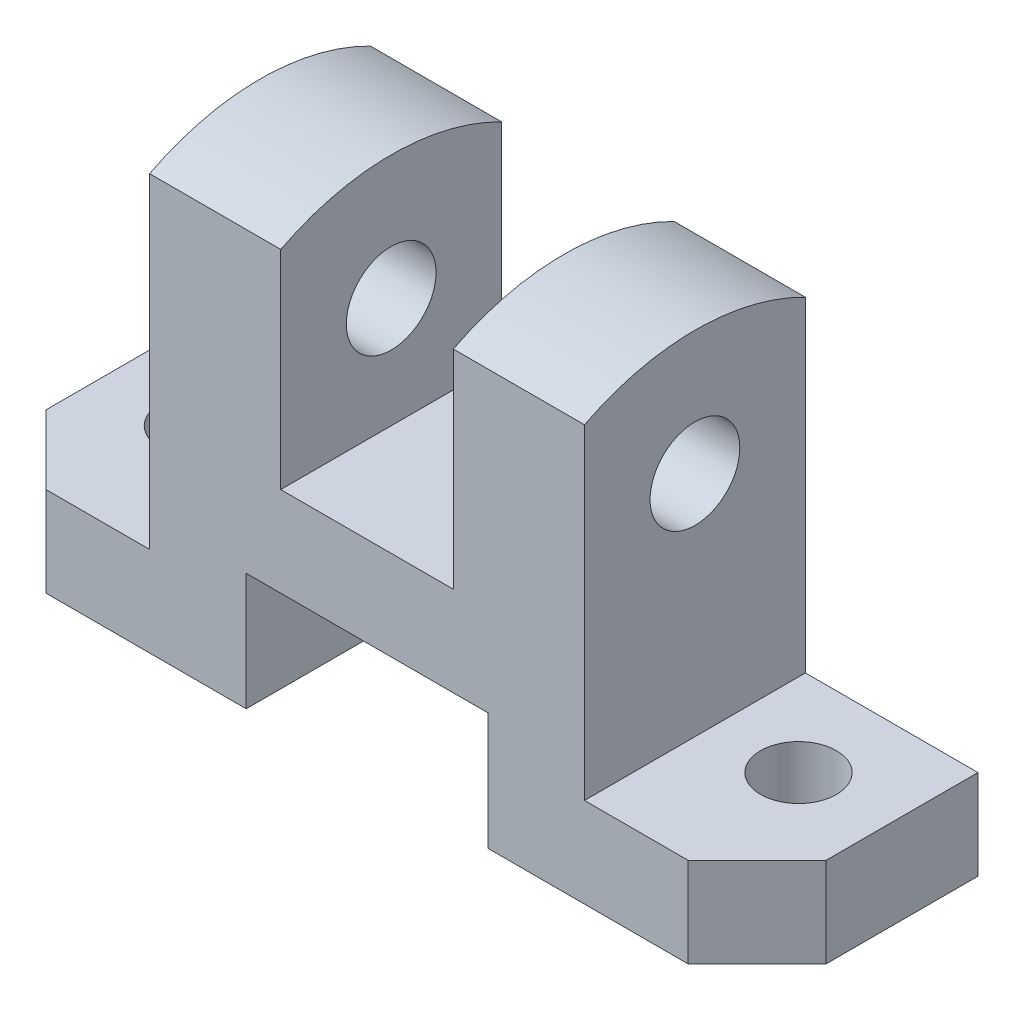
SolidWorks part; units mm, degrees
ref_plane "Front Plane" through (0, 0, 0) normal (0, 0, 1) x (1, 0, 0)
ref_plane "Top Plane" through (0, 0, 0) normal (0, 1, 0) x (1, 0, 0)
ref_plane "Right Plane" through (0, 0, 0) normal (1, 0, 0) x (0, 0, -1)
sketch "Sketch2" plane through (0, 0, 0) normal (0, 1, 0) x (1, 0, 0)
  line L0 (0, 31.6429) -> (0, -36.0714) construction
  line L1 (17.5, 0) -> (56.5, 0)
  line L2 (56.5, 0) -> (56.5, -22)
  line L3 (56.5, -22) -> (46.5, -32)
  line L4 (46.5, -32) -> (17.5, -32)
  line L5 (17.5, 0) -> (17.5, -32)
  line L6 (-17.5, 0) -> (-17.5, -32)
  line L7 (-46.5, -32) -> (-17.5, -32)
  line L8 (-56.5, -22) -> (-46.5, -32)
  line L9 (-56.5, 0) -> (-56.5, -22)
  line L10 (-17.5, 0) -> (-56.5, 0)
  circle A0 centre (43.5, -13) radius 5.5
  circle A1 centre (-43.5, -13) radius 5.5
  dimension "D7" = 11
  dimension "D1" = 10
  dimension "D2" = 39
  dimension "D3" = 32
  dimension "D4" = 45
  dimension "D5" = 13
  dimension "D6" = 13
  dimension "D8" = 35
extrude "Boss-Extrude1" add sketch "Sketch2" along normal blind 13
sketch "Sketch3" plane through (0, 0, 0) normal (0, 0, 1) x (1, 0, 0)
  line L0 (0, 0) -> (0, 22.0533) construction
  line L1 (-17.5, 13) -> (-31.5, 13)
  line L2 (-46.5, 13) -> (-17.5, 13) construction
  line L3 (-31.5, 13) -> (-31.5, 29)
  line L4 (-31.5, 29) -> (-12.5, 29)
  line L6 (-12.5, 17) -> (-17.5, 17)
  line L7 (-17.5, 17) -> (-17.5, 13)
  line L8 (-46.5, 0) -> (-17.5, 0) construction
  line L9 (17.5, 13) -> (31.5, 13)
  line L10 (17.5, 17) -> (17.5, 13)
  line L11 (12.5, 17) -> (17.5, 17)
  line L13 (31.5, 29) -> (12.5, 29)
  line L14 (31.5, 13) -> (31.5, 29)
  line L15 (17.5, 0) -> (46.5, 0) construction
  line L16 (-12.5, 17) -> (12.5, 17)
  line L17 (-12.5, 30) -> (12.5, 30)
  line L18 (-12.5, 30) -> (-12.5, 29)
  line L19 (12.5, 30) -> (12.5, 29)
  point P24 (0, 22.0533)
  dimension "D1" = 17
  dimension "D2" = 19
  dimension "D3" = 25
  dimension "D4" = 29
  dimension "D5" = 13
extrude "Boss-Extrude2" add sketch "Sketch3" along normal blind 32
sketch "Sketch6" plane through (12.5, 0, 0) normal (1, 0, 0) x (0, 0, -1)
  line L0 (-32, 29) -> (0, 29)
  line L1 (0, 29) -> (0, 60.1288)
  line L3 (-32, 60.1288) -> (-32, 29)
  line L4 (-16, 64) -> (-16, 29) construction
  line L5 (-22, 0) -> (0, 0) construction
  arc A0 (0, 60.1288) -> (-32, 60.1288) centre (-16, 29) ccw
  circle A1 centre (-16, 46) radius 6.5
  point P5 (-16, 64)
  dimension "D2" = 13
  dimension "D1" = 35
  dimension "D3" = 46
extrude "Boss-Extrude3" add sketch "Sketch6" along normal blind 19 and the other way blind 44
sketch "Sketch9" plane through (0, 0, 32) normal (0, 0, 1) x (1, 0, 0)
  line L0 (0, 64) -> (0, 17) construction
  line L3 (31.5, 64) -> (-31.5, 64) construction
  line L4 (-17.5, 17) -> (17.5, 17) construction
  line L5 (12.5, 64) -> (-12.5, 64)
  line L6 (-12.5, 64) -> (-12.5, 30)
  line L7 (-12.5, 30) -> (12.5, 30)
  line L8 (12.5, 30) -> (12.5, 64)
  point P6 (0, 0)
  point P9 (0, 64)
  point P12 (0, 64)
  dimension "D1" = 13
  dimension "D2" = 25
extrude "Cut-Extrude1" cut sketch "Sketch9" against normal blind 34
